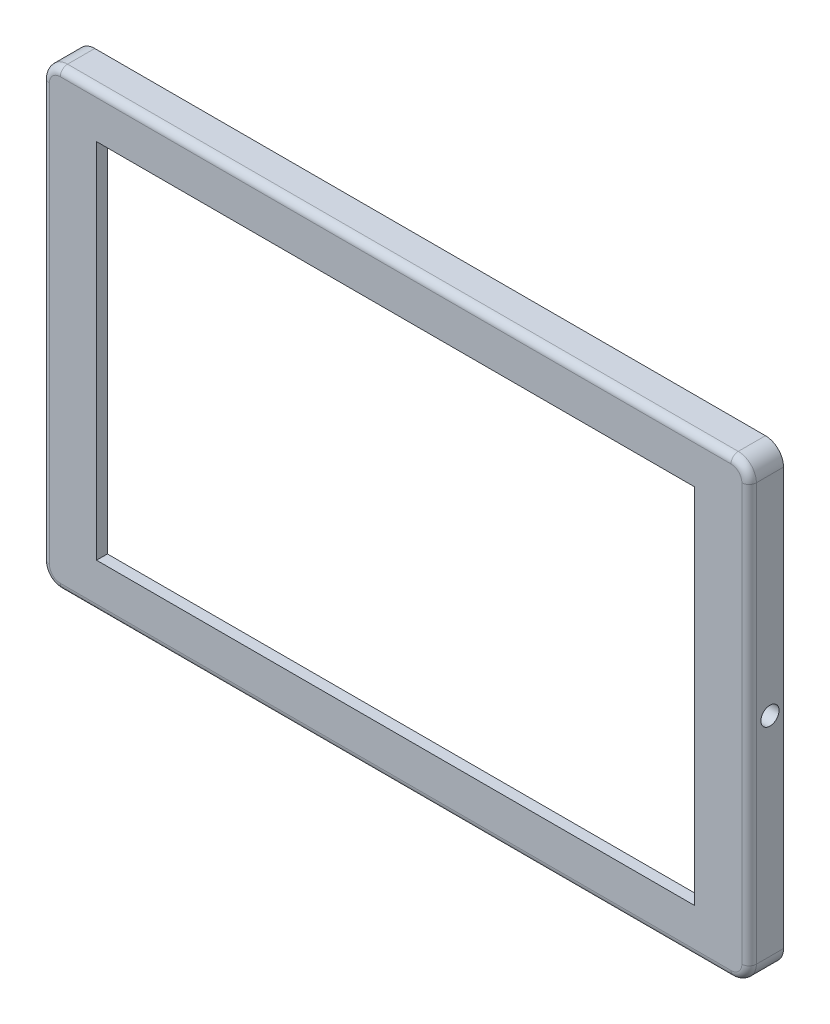
SolidWorks part; units mm, degrees
ref_plane "Front Plane" through (0, 0, 0) normal (0, 0, 1) x (1, 0, 0)
ref_plane "Top Plane" through (0, 0, 0) normal (0, 1, 0) x (1, 0, 0)
ref_plane "Right Plane" through (0, 0, 0) normal (1, 0, 0) x (0, 0, -1)
sketch "Sketch2" plane through (0, 0, 0) normal (0, 0, 1) x (1, 0, 0)
  line L1 (-97.5, 62.5) -> (97.5, 62.5)
  line L2 (-97.5, 62.5) -> (-97.5, -62.5)
  line L3 (-97.5, -62.5) -> (97.5, -62.5)
  line L4 (97.5, 62.5) -> (97.5, -62.5)
  line L5 (-92.5, 57.5) -> (92.5, 57.5)
  line L6 (-92.5, 57.5) -> (-92.5, -57.5)
  line L7 (-92.5, -57.5) -> (92.5, -57.5)
  line L8 (92.5, 57.5) -> (92.5, -57.5)
  point P11 (-97.5, 62.5)
  point P12 (97.5, -62.5)
  dimension "D1" = 5
  dimension "D2" = 5
  dimension "D3" = 5
  dimension "D4" = 5
extrude "Boss-Extrude1" add sketch "Sketch2" along normal blind 9.5
sketch "Sketch3" plane through (0, 0, 9.5) normal (0, 0, 1) x (1, 0, 0)
  line L0 (-82.5, 50) -> (-82.5, -50) construction
  line L1 (-97.5, 62.5) -> (97.5, 62.5)
  line L2 (-97.5, 62.5) -> (-97.5, -62.5)
  line L3 (-97.5, -62.5) -> (97.5, -62.5)
  line L4 (97.5, 62.5) -> (97.5, -62.5)
  line L5 (-82.5, 50) -> (82.5, 50)
  line L6 (-82.5, 50) -> (-82.5, -50)
  line L7 (-82.5, -50) -> (82.5, -50)
  line L8 (82.5, 50) -> (82.5, -50)
  line L9 (82.5, 50) -> (-82.5, 50) construction
  line L10 (82.5, -50) -> (82.5, 50) construction
  line L11 (-82.5, -50) -> (82.5, -50) construction
extrude "Boss-Extrude2" add sketch "Sketch3" against normal blind 3
fillet "Fillet1" radius 5
fillet "Fillet2" radius 2
sketch "Sketch4" plane through (-97.5, 0, 0) normal (-1, 0, 0) x (0, 0, 1)
  line L0 (3.75, 62.5) -> (3.75, -62.5) construction
  line L1 (0, 62.5) -> (7.5, 62.5) construction
  line L2 (7.5, -62.5) -> (0, -62.5) construction
  line L3 (0, 0) -> (7.5, 0) construction
  line L4 (7.5, -57.5) -> (7.5, 57.5) construction
  circle A0 centre (3.75, 0) radius 2.5
  dimension "D1" = 5
extrude "Cut-Extrude1" cut sketch "Sketch4" against normal through all
